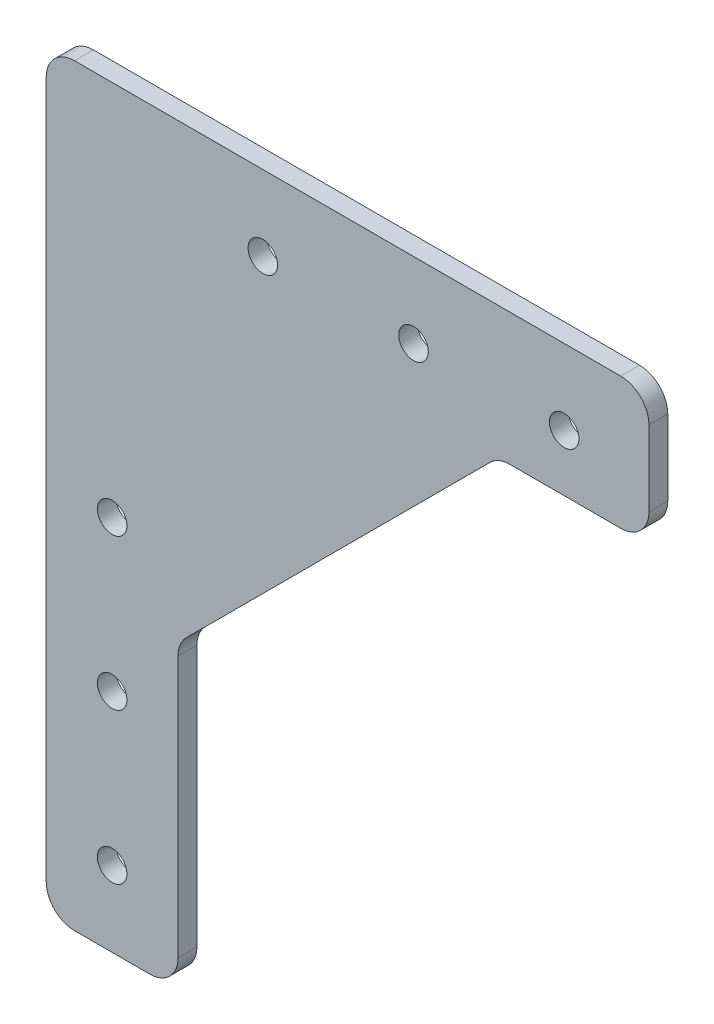
SolidWorks part; units mm, degrees
material "6061-T6 (SS)"
ref_plane "Front Plane" through (0, 0, 0) normal (0, 0, 1) x (1, 0, 0)
ref_plane "Top Plane" through (0, 0, 0) normal (0, 1, 0) x (1, 0, 0)
ref_plane "Right Plane" through (0, 0, 0) normal (1, 0, 0) x (0, 0, -1)
sketch "Sketch1" plane through (0, 0, 0) normal (0, 0, 1) x (1, 0, 0)
  line L8 (0, 0) -> (0, 127)
  line L14 (0, 127) -> (101.6, 127)
  line L15 (101.6, 127) -> (101.6, 104.775)
  line L17 (22.225, 0) -> (0, 0)
  line L18 (11.1125, 0) -> (11.1125, 127) construction
  line L19 (22.225, 0) -> (22.225, 50.8)
  line L20 (22.225, 50.8) -> (76.2, 104.775)
  line L21 (76.2, 104.775) -> (101.6, 104.775)
  circle A7 centre (11.1125, 63.5) radius 2.4892
  circle A8 centre (11.1125, 38.1) radius 2.4892
  circle A9 centre (11.1125, 12.7) radius 2.4892
  circle A11 centre (87.3125, 114.3) radius 2.4892
  circle A12 centre (61.9125, 114.3) radius 2.4892
  circle A13 centre (36.5125, 114.3) radius 2.4892
  point P21 (25.4, 50.981)
  point P22 (25.4, 56.7402)
  point P23 (22.225, 100.5232)
  dimension "D5" = 4.9784
  dimension "D7" = 12.7
  dimension "D1" = 22.225
  dimension "D2" = 127
  dimension "D3" = 101.6
  dimension "D4" = 3
  dimension "D6" = 25.4
  dimension "D8" = 3
  dimension "D9" = 12.7
  dimension "D10" = 25.4
  dimension "D11" = 25.4
  dimension "D12" = 45
  dimension "D13" = 25.4
extrude "Boss-Extrude1" add sketch "Sketch1" along normal mid plane 3.175 contours L18 A7 | A7 L18 | L18 A9 | A9 L18 | A11
fillet "Fillet1" radius 4.7625 7 edges at (0, 127, 0) (0, 0, 0) (101.6, 104.775, 0) (76.2, 104.775, 0) (22.225, 50.8, 0) (22.225, 0, 0) (101.6, 127, 0)
